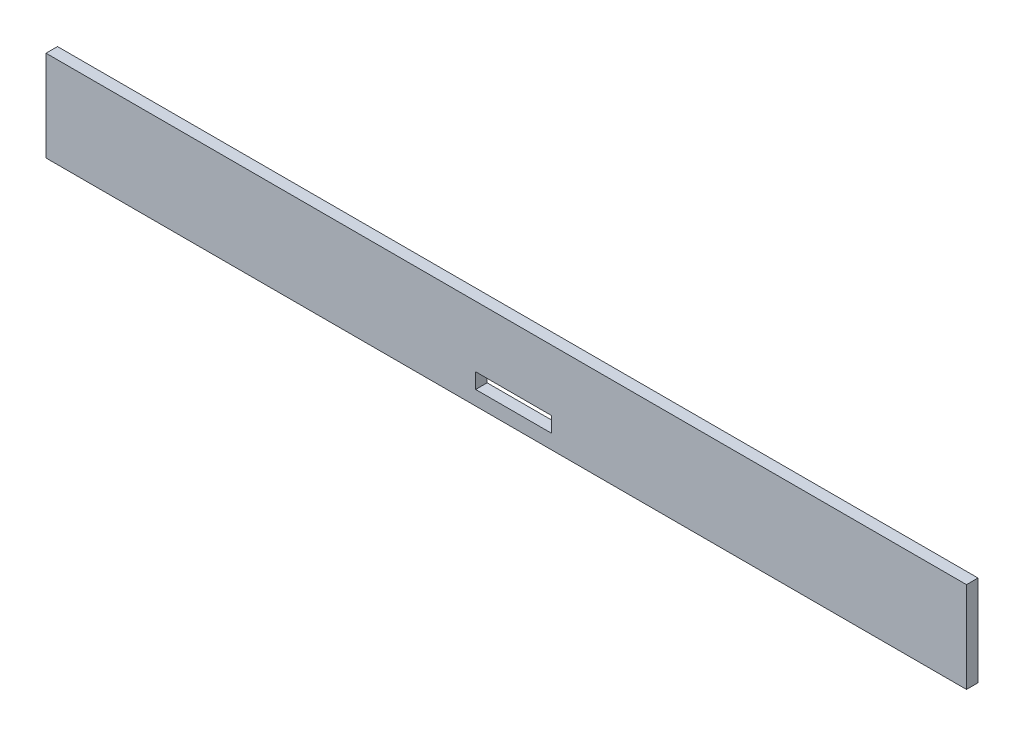
SolidWorks part; units mm, degrees
ref_plane "Front Plane" through (0, 0, 0) normal (0, 0, 1) x (1, 0, 0)
ref_plane "Top Plane" through (0, 0, 0) normal (0, 1, 0) x (1, 0, 0)
ref_plane "Right Plane" through (0, 0, 0) normal (1, 0, 0) x (0, 0, -1)
sketch "Sketch1" plane through (0, 0, 0) normal (0, 0, 1) x (1, 0, 0)
  line L0 (0, 0) -> (203.2, 0)
  line L1 (203.2, 0) -> (203.2, 20.0406)
  line L2 (203.2, 20.0406) -> (0, 20.0406)
  line L3 (0, 20.0406) -> (0, 0)
  line L4 (94.8465, 3.175) -> (111.6105, 3.175)
  line L5 (94.8465, 3.175) -> (94.8465, 6.5617)
  line L6 (94.8465, 6.5617) -> (111.6105, 6.5617)
  line L7 (111.6105, 6.5617) -> (111.6105, 3.175)
  point P8 (103.2285, 3.175)
  dimension "D1" = 20.0406
  dimension "D2" = 203.2
  dimension "D3" = 3.3867
  dimension "D4" = 16.764
  dimension "D5" = 3.175
extrude "Boss-Extrude1" add sketch "Sketch1" along normal blind 2.54
